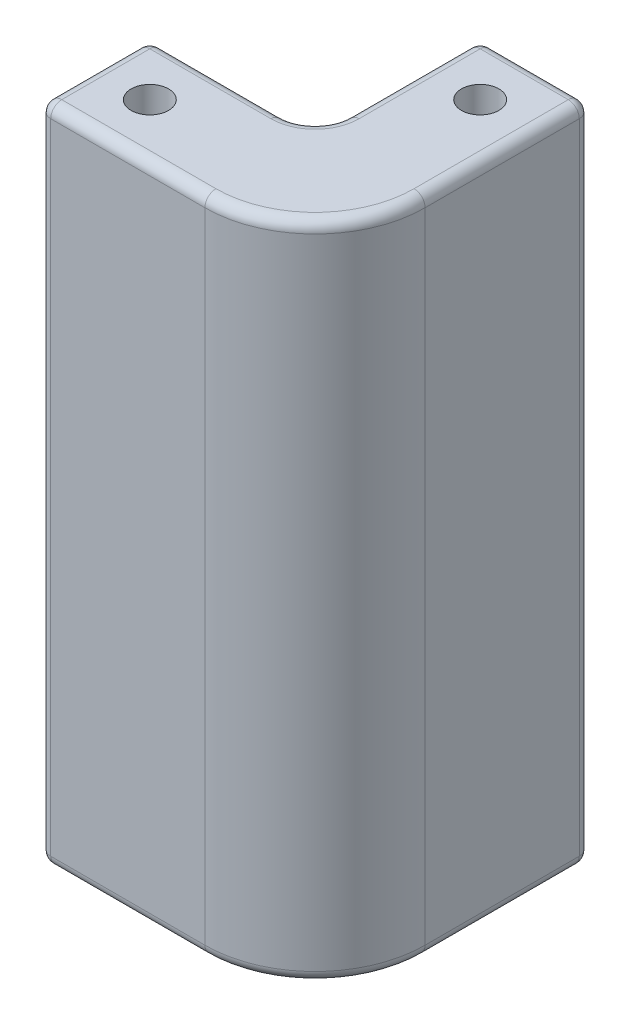
SolidWorks part; units mm, degrees
ref_plane "Front Plane" through (0, 0, 0) normal (0, 0, 1) x (1, 0, 0)
ref_plane "Top Plane" through (0, 0, 0) normal (0, 1, 0) x (1, 0, 0)
ref_plane "Right Plane" through (0, 0, 0) normal (1, 0, 0) x (0, 0, -1)
sketch "Sketch1" plane through (0, 0, 0) normal (0, 1, 0) x (1, 0, 0)
  line L0 (-10, 0) -> (-10, -10) construction
  line L1 (0, 0) -> (-15, 0)
  line L2 (0, 0) -> (0, -10)
  line L3 (0, -10) -> (-15, -10)
  line L4 (-15, 0) -> (-15, -10)
  line L5 (0, 0) -> (10, 0)
  line L6 (0, 0) -> (0, 15)
  line L7 (0, 15) -> (10, 15)
  line L8 (10, 0) -> (10, 15)
  line L9 (0, 10) -> (10, 10) construction
  circle A0 centre (-10, -5) radius 1.7
  circle A1 centre (5, 10) radius 1.7
  arc A2 (10, 0) -> (0, -10) centre (0, 0) cw
  dimension "D5" = 3.4
  dimension "D6" = 3.4
  dimension "D1" = 10
  dimension "D2" = 10
  dimension "D3" = 15
  dimension "D4" = 15
  dimension "D7" = 5
  dimension "D8" = 5
extrude "Boss-Extrude1" add sketch "Sketch1" along normal blind 60 contours L1 L4 L3 L2 A0 | A2 L5 L2 | L5 L8 L7 L6 A1
sketch "Sketch2" plane through (0, 0, 0) normal (-1, 0, 0) x (0, 0, 1)
  line L0 (-10, 60) -> (-10, 0) construction
  line L1 (0, 60) -> (-15, 60) construction
  line L2 (0, 0) -> (-15, 0) construction
  line L3 (-15, 60) -> (-15, 0) construction
  line L5 (-12.9, 56.3) -> (-7.1, 56.3)
  line L6 (-12.9, 56.3) -> (-12.9, 53.7)
  line L7 (-12.9, 53.7) -> (-7.1, 53.7)
  line L8 (-7.1, 56.3) -> (-7.1, 53.7)
  line L9 (-12.9, 56.3) -> (-7.1, 53.7) construction
  line L10 (-12.9, 53.7) -> (-7.1, 56.3) construction
  line L11 (-12.9, 6.3) -> (-7.1, 6.3)
  line L12 (-12.9, 6.3) -> (-12.9, 3.7)
  line L13 (-12.9, 3.7) -> (-7.1, 3.7)
  line L14 (-7.1, 6.3) -> (-7.1, 3.7)
  line L15 (-12.9, 6.3) -> (-7.1, 3.7) construction
  line L16 (-12.9, 3.7) -> (-7.1, 6.3) construction
  point P8 (-10, 55)
  point P13 (-10, 5)
  dimension "D1" = 5
  dimension "D2" = 2.6
  dimension "D3" = 5.8
  dimension "D4" = 5
  dimension "D5" = 5.8
  dimension "D6" = 2.6
  dimension "D7" = 5
extrude "Cut-Extrude1" cut sketch "Sketch2" against normal blind 9
sketch "Sketch3" plane through (0, 0, 0) normal (0, 0, -1) x (-1, 0, 0)
  line L0 (10, 60) -> (10, 0) construction
  line L1 (0, 60) -> (15, 60) construction
  line L2 (0, 0) -> (15, 0) construction
  line L3 (15, 60) -> (15, 0) construction
  line L5 (7.1, 56.3) -> (12.9, 56.3)
  line L6 (7.1, 56.3) -> (7.1, 53.7)
  line L7 (7.1, 53.7) -> (12.9, 53.7)
  line L8 (12.9, 56.3) -> (12.9, 53.7)
  line L9 (7.1, 56.3) -> (12.9, 53.7) construction
  line L10 (7.1, 53.7) -> (12.9, 56.3) construction
  line L11 (7.1, 6.3) -> (12.9, 6.3)
  line L12 (7.1, 6.3) -> (7.1, 3.7)
  line L13 (7.1, 3.7) -> (12.9, 3.7)
  line L14 (12.9, 6.3) -> (12.9, 3.7)
  line L15 (7.1, 6.3) -> (12.9, 3.7) construction
  line L16 (7.1, 3.7) -> (12.9, 6.3) construction
  point P8 (10, 55)
  point P13 (10, 5)
  dimension "D1" = 5
  dimension "D2" = 5.8
  dimension "D3" = 2.6
  dimension "D4" = 5.8
  dimension "D5" = 2.6
  dimension "D6" = 5
  dimension "D7" = 5
extrude "Cut-Extrude2" cut sketch "Sketch3" against normal blind 9
fillet "Fillet1" radius 1 4 edges at (-15, 30, 10) (-15, 30, 0) (0, 30, -15) (10, 30, -15)
fillet "Fillet3" radius 3 1 edges at (0, 30, 0)
fillet "Fillet4" radius 1 24 edges at (10, 0, -7) (10, 60, -7) (9.7071, 60, -14.7071) (9.7071, 0, -14.7071) (5, 0, -15) (5, 60, -15) (0.2929, 60, -14.7071) (0.2929, 0, -14.7071) (0, 0, -8.5) (0, 60, -8.5) (-0.8787, 60, -0.8787) (-0.8787, 0, -0.8787) (7.0711, 0, 7.0711) (7.0711, 60, 7.0711) (-7, 60, 10) (-7, 0, 10) (-14.7071, 60, 9.7071) (-14.7071, 0, 9.7071) (-15, 0, 5) (-15, 60, 5) (-14.7071, 60, 0.2929) (-14.7071, 0, 0.2929) (-8.5, 60, 0) (-8.5, 0, 0)
